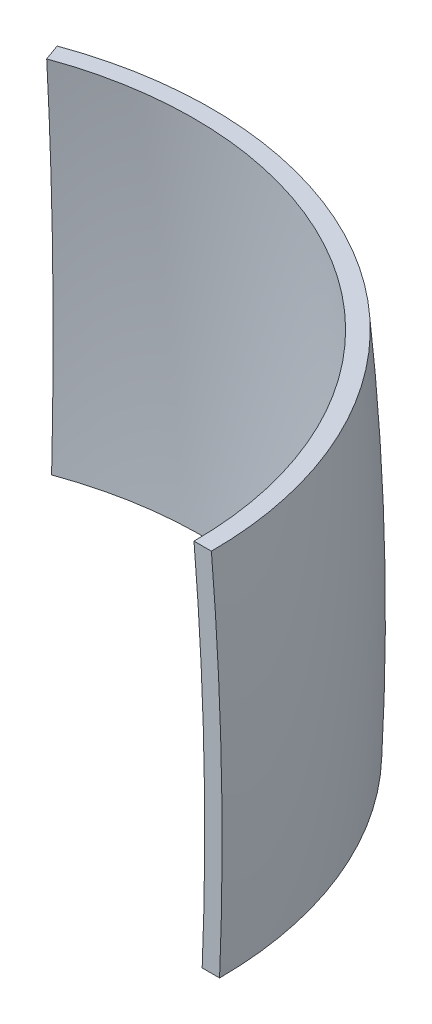
SolidWorks part; units mm, degrees
ref_plane "Спереди" through (0, 0, 0) normal (0, 0, 1) x (1, 0, 0)
ref_plane "Сверху" through (0, 0, 0) normal (0, 1, 0) x (1, 0, 0)
ref_plane "Справа" through (0, 0, 0) normal (1, 0, 0) x (0, 0, -1)
sketch "Эскиз1" plane through (0, 0, 0) normal (0, 0, 1) x (1, 0, 0)
  line L8 (0, 0) -> (0, 226.6388) construction
  line L9 (45, 14.9986) -> (43, 14.9968)
  line L10 (42.0593, 56.9978) -> (44.0593, 56.9978)
  arc A0 (44.0593, 56.9978) -> (45, 14.9986) centre (-281.2924, 28.7006) cw
  arc A3 (42.0593, 56.9978) -> (43, 14.9968) centre (-281.6894, 28.7359) cw
  dimension "D1" = 326.58
  dimension "D2" = 43
  dimension "D6" = 2
  dimension "D7" = 2
  dimension "D8" = 42
revolve "Повернуть1" add sketch "Эскиз1" angle 110 about L8
